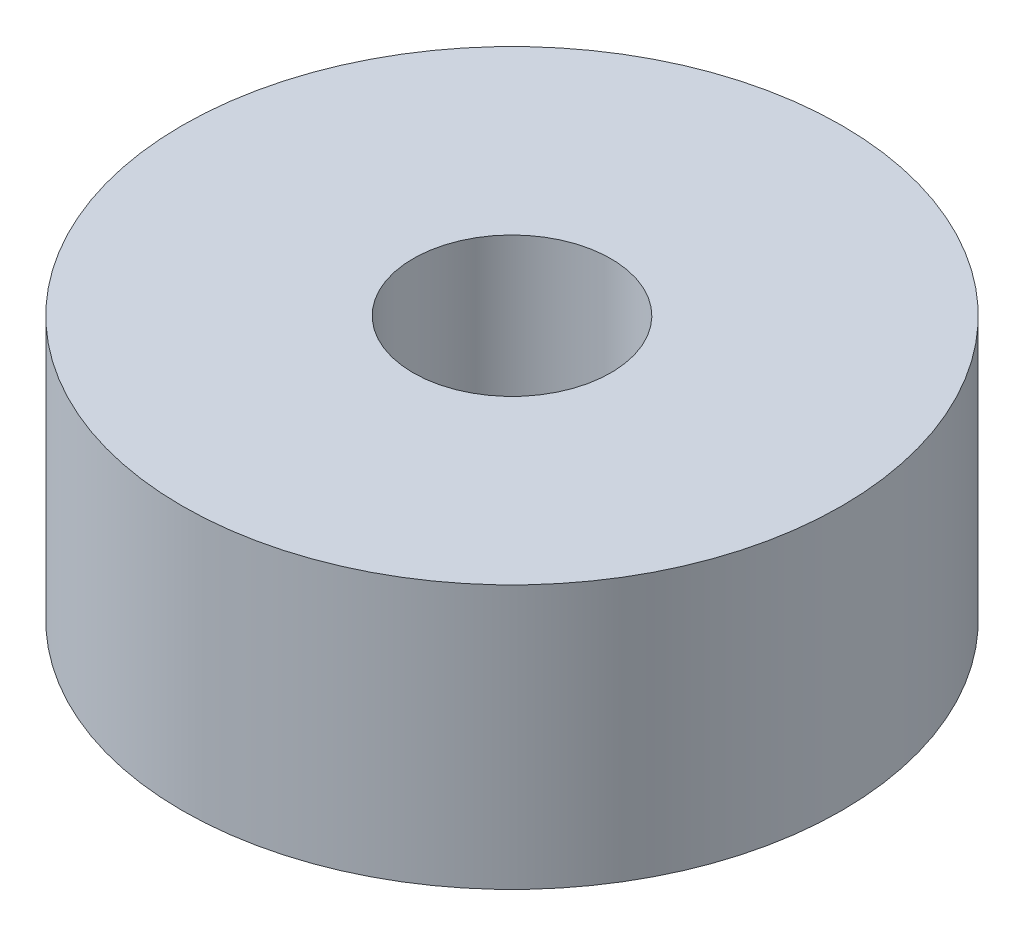
SolidWorks part; units mm, degrees
ref_plane "Alzado" through (0, 0, 0) normal (0, 0, 1) x (1, 0, 0)
ref_plane "Planta" through (0, 0, 0) normal (0, 1, 0) x (1, 0, 0)
ref_plane "Vista lateral" through (0, 0, 0) normal (1, 0, 0) x (0, 0, -1)
sketch "Croquis1" plane through (0, 0, 0) normal (0, 1, 0) x (1, 0, 0)
  circle A0 centre (0, 0) radius 5
  circle A1 centre (0, 0) radius 1.5
extrude "Saliente-Extruir1" add sketch "Croquis1" along normal blind 4
